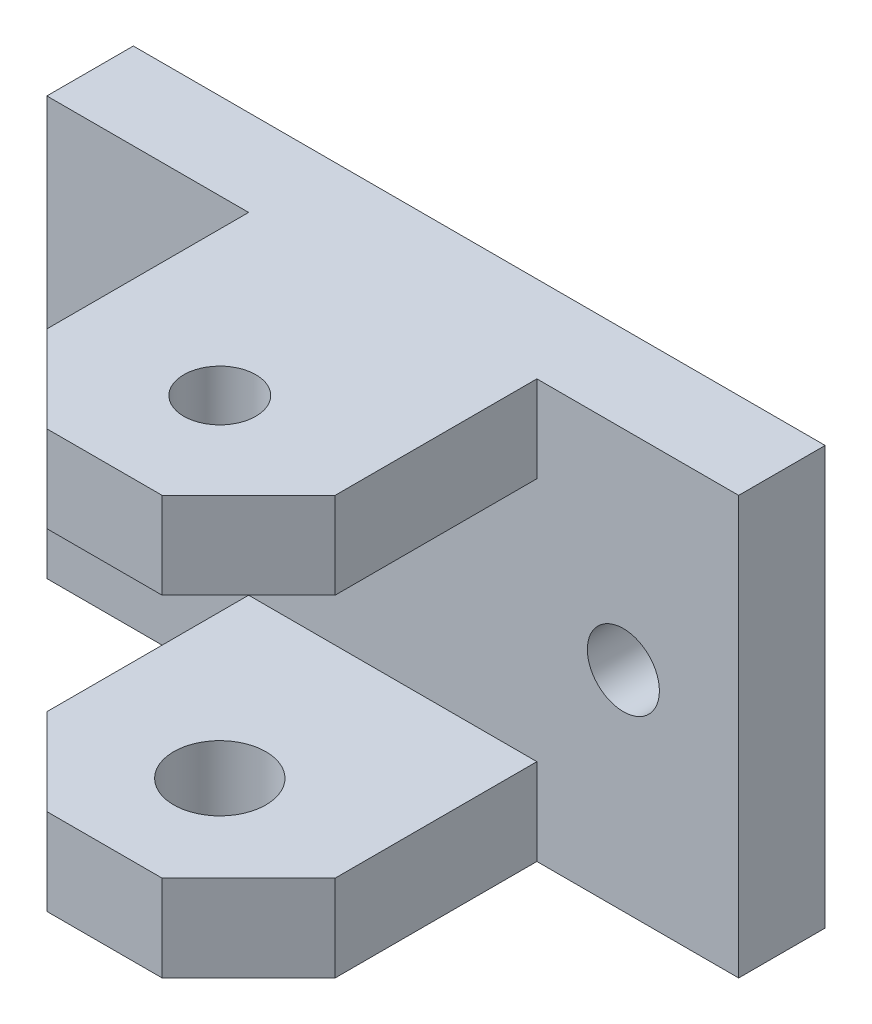
SolidWorks part; units mm, degrees
material "1023 碳钢板 (SS)"
ref_plane "前视基准面" through (0, 0, 0) normal (0, 0, 1) x (1, 0, 0)
ref_plane "上视基准面" through (0, 0, 0) normal (0, 1, 0) x (1, 0, 0)
ref_plane "右视基准面" through (0, 0, 0) normal (1, 0, 0) x (0, 0, -1)
sketch "草图1" plane through (0, 0, 0) normal (0, 0, 1) x (1, 0, 0)
  line L1 (-12, -7.25) -> (12, -7.25)
  line L2 (-12, -7.25) -> (-12, 7.25)
  line L3 (-12, 7.25) -> (12, 7.25)
  line L4 (12, -7.25) -> (12, 7.25)
  line L5 (-12, -7.25) -> (12, 7.25) construction
  line L6 (-12, 7.25) -> (12, -7.25) construction
  point P0 (0, 0)
  dimension "D1" = 24
  dimension "D2" = 14.5
extrude "凸台-拉伸1" add sketch "草图1" along normal blind 3
sketch "草图2" plane through (0, -7.25, 0) normal (0, -1, 0) x (1, 0, 0)
  line L0 (0, 0) -> (0, 14)
  line L1 (-12, 0) -> (12, 0) construction
  dimension "D1" = 14
extrude "拉伸-薄壁1" add sketch "草图2" against normal blind 3 thin thin type mid plane wall 10
mirror "镜向1" about plane through (0, 0, 0) normal (0, 1, 0) of "拉伸-薄壁1"
sketch "草图3" plane through (0, -7.25, 0) normal (0, -1, 0) x (1, 0, 0)
  line L0 (-12, 0) -> (12, 0) construction
  circle A0 centre (0, 9) radius 1.6
  point P4 (0, 0)
  dimension "D1" = 3.2
  dimension "D2" = 9
extrude "切除-拉伸1" cut sketch "草图3" against normal up to next
sketch "草图4" plane through (0, 7.25, 0) normal (0, 1, 0) x (1, 0, 0)
  circle A0 centre (0, -9) radius 1.6 construction
  circle A1 centre (0, -9) radius 1.6
hole_wizard "M3 螺纹孔2" positions "3D草图1" profile "草图6" tap size "M3" standard "GB" end condition up to next
sketch3d "3D草图1"
  point P0 (0, 7.25, 9)
sketch "草图6" plane through (0, 7.25, 9) normal (1, 0, 0) x (0, 0, 1)
  line L0 (0, 0) -> (0, 3)
  line L1 (0, 3) -> (1.25, 3)
  line L2 (1.25, 3) -> (1.25, 0)
  line L5 (1.25, 0) -> (0, 0)
  line L11 (0, -6.35) -> (0, 107.95) construction
  dimension "通孔螺纹孔钻头直径" = 2.5
  dimension "通孔螺纹孔钻头深度" = 3
cosmetic thread "孔螺蚊线3" parameters "D2"=3
sketch "草图7" plane through (0, 0, 0) normal (0, 0, -1) x (-1, 0, 0)
  line L1 (-4.5, -3.4858) -> (4.5, -3.4858) construction
  line L2 (-4.5, -3.4858) -> (-4.5, 3.4858) construction
  line L3 (-4.5, 3.4858) -> (4.5, 3.4858) construction
  line L4 (4.5, -3.4858) -> (4.5, 3.4858) construction
  line L5 (-4.5, -3.4858) -> (4.5, 3.4858) construction
  line L6 (-4.5, 3.4858) -> (4.5, -3.4858) construction
  point P0 (0, 0)
  point P5 (-4.5, 0)
  point P6 (4.5, 0)
  dimension "D1" = 9
hole_wizard "M3 螺纹孔1" positions "草图9" profile "草图8" tap size "M3" standard "GB" end condition up to next
sketch "草图9" plane through (0, 0, 3) normal (0, 0, 1) x (1, 0, 0)
  line L0 (-5, 4.25) -> (5, 4.25) construction
  line L1 (-12, 7.25) -> (-12, -7.25) construction
  point P0 (-8, 0)
  point P2 (8, 0)
  point P5 (0, 4.25)
  point P10 (-12, 0)
  dimension "D1" = 16
  dimension "D2" = 8
sketch "草图8" plane through (-8, 0, 3) normal (1, 0, 0) x (0, -1, 0)
  line L0 (0, 0) -> (0, 3)
  line L1 (0, 3) -> (1.25, 3)
  line L2 (1.25, 3) -> (1.25, 0)
  line L5 (1.25, 0) -> (0, 0)
  line L11 (0, -6.35) -> (0, 107.95) construction
  dimension "通孔螺纹孔钻头直径" = 2.5
  dimension "通孔螺纹孔钻头深度" = 3
cosmetic thread "孔螺蚊线1" parameters "D2"=3
cosmetic thread "孔螺蚊线2" parameters "D2"=3
sketch "草图10" plane through (0, 0, 0) normal (0, 0, -1) x (-1, 0, 0)
  line L0 (12, -7.25) -> (-12, -7.25) construction
  line L1 (-12, 7.25) -> (-11.5, 7.25)
  line L2 (-12, 7.25) -> (-12, -7.25)
  line L3 (-12, -7.25) -> (-11.5, -7.25)
  line L4 (-11.5, 7.25) -> (-11.5, -7.25)
  line L5 (-12, 7.25) -> (12, 7.25) construction
  line L6 (12, -7.25) -> (11.5, -7.25)
  line L7 (12, -7.25) -> (12, 7.25)
  line L8 (12, 7.25) -> (11.5, 7.25)
  line L9 (11.5, -7.25) -> (11.5, 7.25)
  circle A1 centre (-8, 0) radius 1.25 construction
  circle A2 centre (8, 0) radius 1.25 construction
  dimension "D2" = 3.5
  dimension "D1" = 3.5
extrude "切除-拉伸2" cut sketch "草图10" against normal through all
sketch "草图11" plane through (0, -7.25, 0) normal (0, -1, 0) x (1, 0, 0)
  line L0 (5, 3) -> (5, 14) construction
  line L1 (-5, 14) -> (5, 14)
  line L2 (-5, 14) -> (-5, 13)
  line L3 (-5, 13) -> (5, 13)
  line L4 (5, 14) -> (5, 13)
  circle A0 centre (0, 9) radius 1.25 construction
  dimension "D1" = 4
extrude "切除-拉伸3" cut sketch "草图11" against normal through all
chamfer "倒角1" distance 3 angle 45 4 edges at (5, 5.75, 13) (5, -5.75, 13) (-5, -5.75, 13) (-5, 5.75, 13)
sketch "草图12" plane through (0, 0, 3) normal (0, 0, 1) x (1, 0, 0)
  line L0 (5, -7.25) -> (11.5, -7.25) construction
  line L1 (11.5, 7.25) -> (12, 7.25)
  line L2 (11.5, 7.25) -> (11.5, -7.25)
  line L3 (11.5, -7.25) -> (12, -7.25)
  line L4 (12, 7.25) -> (12, -7.25)
  dimension "D1" = 12
extrude "凸台-拉伸2" add sketch "草图12" against normal up to surface (3 mm away) up to face at (0, 0, 0)
mirror "镜向2" about plane through (0, 0, 0) normal (1, 0, 0) of "凸台-拉伸2"
